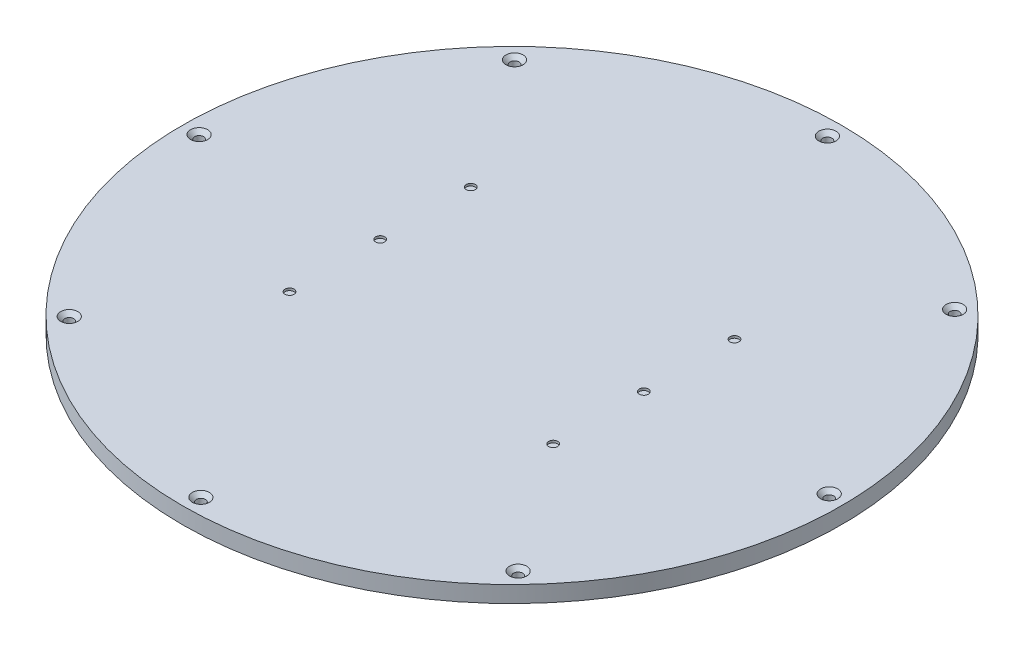
SolidWorks part; units mm, degrees
ref_plane "Front Plane" through (0, 0, 0) normal (0, 0, 1) x (1, 0, 0)
ref_plane "Top Plane" through (0, 0, 0) normal (0, 1, 0) x (1, 0, 0)
ref_plane "Right Plane" through (0, 0, 0) normal (1, 0, 0) x (0, 0, -1)
sketch "Sketch1" plane through (0, 0, 0) normal (0, 1, 0) x (1, 0, 0)
  circle A0 centre (0, 0) radius 200
  dimension "D1" = 400
extrude "Boss-Extrude1" add sketch "Sketch1" along normal blind 10
hole_wizard "CSK for M5 Flat Head Machine Screw1" positions "Sketch9" profile "Sketch10" countersink size "M5" standard "ANSI Metric" end condition through all
sketch "Sketch9" plane through (0, 10, 0) normal (0, 1, 0) x (1, 0, 0)
  point P0 (-190, 0.1136)
  point P2 (1.4174, 189.9947)
  point P4 (189.9834, 2.5128)
  point P6 (1.1879, -189.9963)
  point P8 (-133.8121, -134.8864)
  point P10 (-133.5826, 135.1136)
  point P12 (131.1115, 137.5128)
  point P14 (136.1879, -132.4872)
  dimension "D1" = 190
  dimension "D2" = 190
  dimension "D3" = 190
  dimension "D4" = 190
  dimension "D5" = 190
  dimension "D6" = 190
  dimension "D7" = 190
  dimension "D8" = 190
  dimension "D9" = 135
  dimension "D10" = 135
  dimension "D11" = 135
  dimension "D12" = 135
  dimension "D13" = 135
  dimension "D14" = 135
  dimension "D15" = 135
  dimension "D16" = 129.694
sketch "Sketch10" plane through (-190, 10, -0.1136) normal (1, 0, 0) x (0, 0, 1)
  line L0 (0, 0) -> (0, 10)
  line L1 (0, 10) -> (2.75, 10)
  line L2 (2.75, 10) -> (2.75, 2.45)
  line L3 (2.75, 2.45) -> (5.2, 0)
  line L5 (5.2, 0) -> (0, 0)
  line L6 (-2.75, 2.45) -> (-5.2, 0) construction
  line L11 (0, -6.35) -> (0, 107.95) construction
  dimension "Thru Hole Dia." = 5.5
  dimension "Thru Hole Depth" = 10
  dimension "Near C'Sink Dia." = 10.4
  dimension "Near C'Sink Angle" = 90
shell "Shell1" thickness 1.4
hole_wizard "CSK for M5 Flat Head Machine Screw2" positions "Sketch11" profile "Sketch12" countersink size "M5" standard "ANSI Metric" end condition through all
sketch "Sketch11" plane through (0, 0, 0) normal (0, -1, 0) x (-1, 0, 0)
  point P0 (-80, 0)
  point P2 (-80, 55)
  point P4 (-80, -55)
  point P6 (80, 0)
  point P8 (80, 55)
  point P10 (80, -55)
  point P15 (0, 0)
  point P16 (0, 0)
  point P17 (0, 0)
  point P18 (0, 0)
  dimension "D1" = 80
  dimension "D2" = 55
  dimension "D3" = 55
  dimension "D4" = 160
  dimension "D5" = 0
  dimension "D6" = 160
  dimension "D7" = 160
  dimension "D8" = 55
  dimension "D9" = 55
  dimension "D10" = 80
  dimension "D11" = 80
  dimension "D12" = 80
sketch "Sketch12" plane through (80, 0, 0) normal (1, 0, 0) x (0, 0, -1)
  line L0 (0, 0) -> (0, 10)
  line L1 (0, 10) -> (2.75, 10)
  line L2 (2.75, 10) -> (2.75, 2.45)
  line L3 (2.75, 2.45) -> (5.2, 0)
  line L5 (5.2, 0) -> (0, 0)
  line L6 (-2.75, 2.45) -> (-5.2, 0) construction
  line L11 (0, -6.35) -> (0, 107.95) construction
  dimension "Thru Hole Dia." = 5.5
  dimension "Thru Hole Depth" = 10
  dimension "Near C'Sink Dia." = 10.4
  dimension "Near C'Sink Angle" = 90
